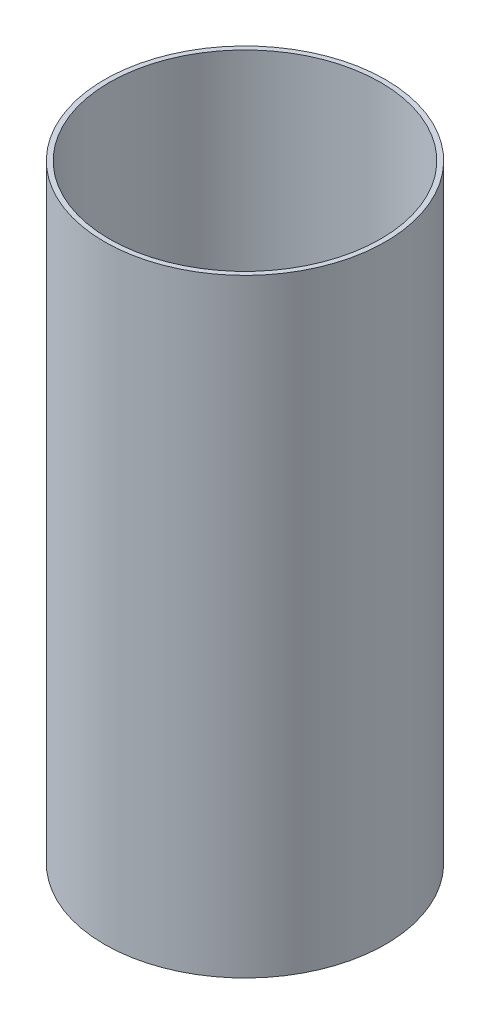
SolidWorks part; units mm, degrees
material "Acrylic (Medium-high impact)"
ref_plane "Front Plane" through (0, 0, 0) normal (0, 0, 1) x (1, 0, 0)
ref_plane "Top Plane" through (0, 0, 0) normal (0, 1, 0) x (1, 0, 0)
ref_plane "Right Plane" through (0, 0, 0) normal (1, 0, 0) x (0, 0, -1)
sketch "Sketch1" plane through (0, 0, 0) normal (0, 1, 0) x (1, 0, 0)
  circle A0 centre (0, 0) radius 92.075
  circle A1 centre (0, 0) radius 88.9
  dimension "D1" = 184.15
  dimension "D2" = 177.8
extrude "Boss-Extrude1" add sketch "Sketch1" along normal mid plane 398.78
ref_plane "Plane1" through (0, 0, 92.075) normal (0, 0, 1) x (1, 0, 0)
sketch "Sketch3" plane through (0, 0, 92.075) normal (0, 0, 1) x (1, 0, 0)
  line L0 (0, -55) -> (0, 55) construction
  line L1 (-92.075, -199.39) -> (92.075, -199.39) construction
  circle A0 centre (0, -193.04) radius 1.4351
  dimension "D1" = 2.8702
  dimension "D2" = 6.35
extrude "Cut-Extrude1" [suppressed] cut sketch "Sketch3" against normal blind 19.304
pattern_circular "CirPattern1" [suppressed] count 12 over 360
mirror "Mirror1" [suppressed] about plane through (0, 0, 0) normal (0, 1, 0)
sketch "Sketch4" [suppressed] plane through (0, 0, 93.6625) normal (0, 0, 1) x (1, 0, 0)
  line L0 (0, -103.0288) -> (0, 103.0288) construction
  circle A0 centre (0, 64.3636) radius 1.4351
  circle A1 centre (0, -64.3636) radius 1.4351
  circle A2 centre (0, 193.04) radius 1.4351 construction
  circle A3 centre (0, -193.04) radius 1.4351 construction
  dimension "D1" = 128.6764
  dimension "D2" = 128.6764
  dimension "D3" = 2.8702
  dimension "D4" = 2.8702
extrude "Cut-Extrude2" [suppressed] cut sketch "Sketch4" against normal blind 43.18
pattern_circular "CirPattern2" [suppressed] count 3 over 360
